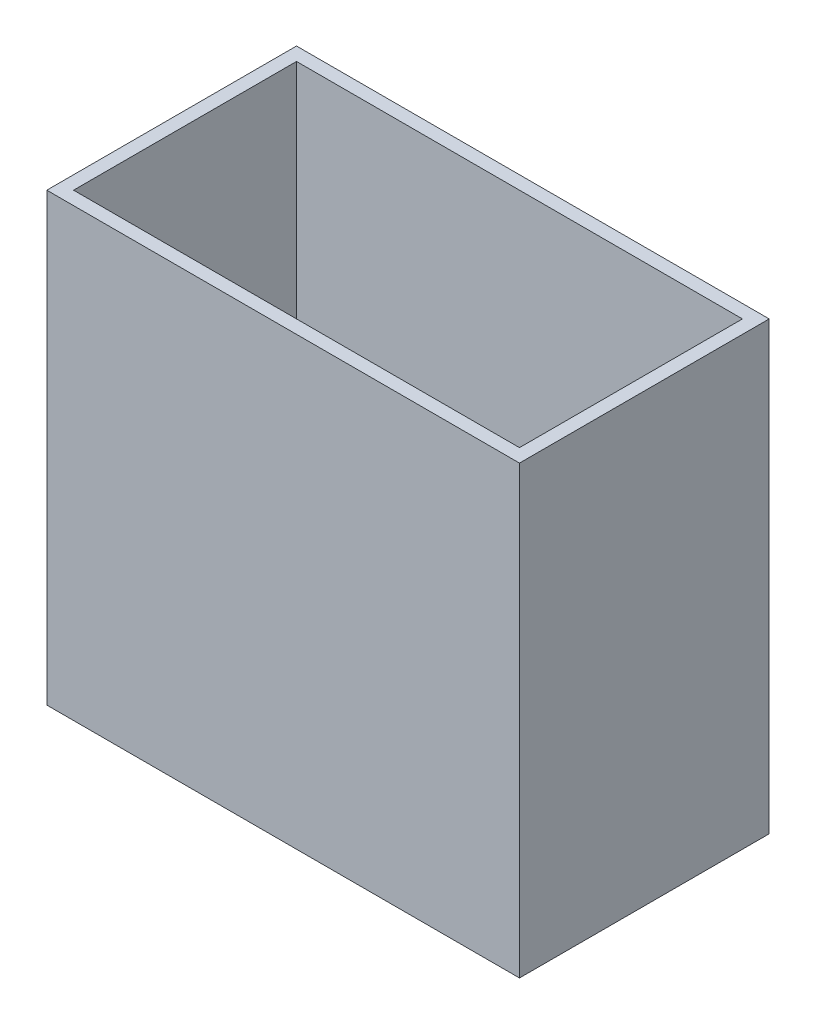
SolidWorks part; units mm, degrees
ref_plane "前基準面" through (0, 0, 0) normal (0, 0, 1) x (1, 0, 0)
ref_plane "上基準面" through (0, 0, 0) normal (0, 1, 0) x (1, 0, 0)
ref_plane "右基準面" through (0, 0, 0) normal (1, 0, 0) x (0, 0, -1)
sketch "草圖1" plane through (0, 0, 0) normal (0, 1, 0) x (1, 0, 0)
  line L0 (3, 3) -> (3, 53)
  line L1 (0, 0) -> (106, 0)
  line L2 (0, 0) -> (0, 56)
  line L3 (0, 56) -> (106, 56)
  line L4 (106, 0) -> (106, 56)
  line L5 (3, 53) -> (103, 53)
  line L6 (103, 3) -> (103, 53)
  line L7 (3, 3) -> (103, 3)
  dimension "D1" = 56
  dimension "D2" = 106
  dimension "D3" = 3
extrude "填料-伸長1" add sketch "草圖1" along normal blind 100
